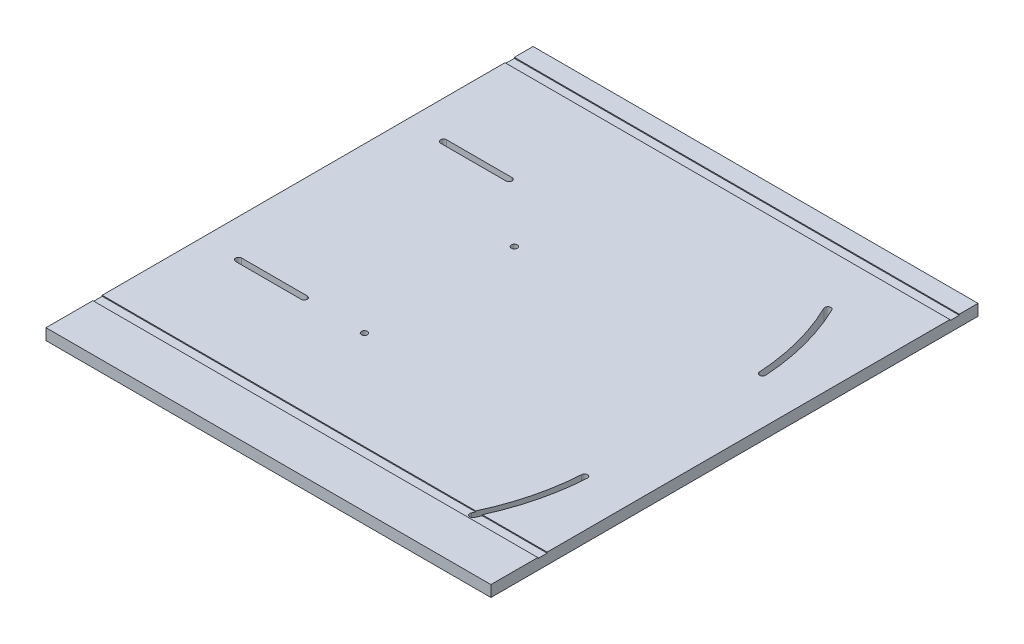
SolidWorks part; units mm, degrees
ref_plane "Front" through (0, 0, 0) normal (0, 0, 1) x (1, 0, 0)
ref_plane "Top" through (0, 0, 0) normal (0, 1, 0) x (1, 0, 0)
ref_plane "Right" through (0, 0, 0) normal (1, 0, 0) x (0, 0, -1)
sketch "Sketch1" plane through (0, 0, 0) normal (0, 1, 0) x (1, 0, 0)
  line L1 (-301.625, 330.2) -> (301.625, 330.2)
  line L2 (-301.625, 330.2) -> (-301.625, -330.2)
  line L3 (-301.625, -330.2) -> (301.625, -330.2)
  line L4 (301.625, 330.2) -> (301.625, -330.2)
  line L5 (-301.625, 330.2) -> (301.625, -330.2) construction
  line L6 (-301.625, -330.2) -> (301.625, 330.2) construction
  point P0 (0, 0)
  dimension "D1" = 660.4
  dimension "D2" = 603.25
extrude "Boss-Extrude1" add sketch "Sketch1" along normal blind 19.05
chamfer "Chamfer1" distance 3.81 angle 45 4 edges at (0, 0, -330.2) (-301.625, 0, 0) (0, 0, 330.2) (301.625, 0, 0)
sketch "Sketch8" plane through (0, 19.05, 0) normal (0, 1, 0) x (1, 0, 0)
  line L0 (301.625, 330.2) -> (-301.625, 330.2) construction
  line L1 (-103.505, 330.2) -> (-106.045, 330.2)
  line L2 (-103.505, 330.2) -> (-103.505, -330.2)
  line L3 (-103.505, -330.2) -> (-106.045, -330.2)
  line L4 (-106.045, 330.2) -> (-106.045, -330.2)
  line L5 (-301.625, -330.2) -> (301.625, -330.2) construction
  line L6 (301.625, -330.2) -> (301.625, 330.2) construction
  dimension "D1" = 2.54
  dimension "D2" = 405.13
sketch "Sketch3" plane through (0, 19.05, 0) normal (0, 1, 0) x (1, 0, 0)
  line L0 (-49.9149, 311.15) -> (-49.9149, -273.05) construction
  line L1 (301.625, -330.2) -> (301.625, 330.2) construction
  line L2 (-250.825, 157.9404) -> (-161.925, 157.9404) construction
  line L3 (-250.825, 162.0044) -> (-161.925, 162.0044)
  line L4 (-250.825, 153.8764) -> (-161.925, 153.8764)
  line L5 (-49.9149, 19.05) -> (-301.625, 19.05) construction
  line L6 (-250.825, -119.8404) -> (-161.925, -119.8404) construction
  line L7 (-250.825, -123.9044) -> (-161.925, -123.9044)
  line L8 (-250.825, -115.7764) -> (-161.925, -115.7764)
  line L9 (-301.625, 330.2) -> (-301.625, -330.2) construction
  line L11 (-301.625, 311.15) -> (301.625, 311.15) construction
  line L12 (301.625, 330.2) -> (-301.625, 330.2) construction
  line L13 (-301.625, -273.05) -> (301.625, -273.05) construction
  arc A0 (-250.825, 162.0044) -> (-250.825, 153.8764) centre (-250.825, 157.9404) ccw
  arc A1 (-161.925, 153.8764) -> (-161.925, 162.0044) centre (-161.925, 157.9404) ccw
  arc A2 (-250.825, -123.9044) -> (-250.825, -115.7764) centre (-250.825, -119.8404) cw
  arc A3 (-161.925, -115.7764) -> (-161.925, -123.9044) centre (-161.925, -119.8404) cw
  point P7 (-206.375, 157.9404)
  point P16 (-206.375, -119.8404)
  dimension "D1" = 8.128
  dimension "D2" = 88.9
  dimension "D3" = 95.25
  dimension "D4" = 19.05
  dimension "D5" = 584.2
extrude "Cut-Extrude2" cut sketch "Sketch3" against normal through all
sketch "Sketch6" plane through (0, 19.05, 0) normal (0, 1, 0) x (1, 0, 0)
  line L0 (-79.375, 82.55) -> (-79.375, -120.65) construction
  line L1 (301.625, -330.2) -> (301.625, 330.2) construction
  line L2 (-301.625, -330.2) -> (301.625, -330.2) construction
  circle A0 centre (-79.375, 82.55) radius 4.064
  circle A1 centre (-79.375, -120.65) radius 4.064
  dimension "D1" = 8.128
  dimension "D2" = 203.2
  dimension "D3" = 381
  dimension "D4" = 209.55
extrude "Cut-Extrude5" cut sketch "Sketch6" against normal through all
sketch "Sketch7" plane through (0, 19.05, 0) normal (0, 1, 0) x (1, 0, 0)
  line L0 (-79.375, 82.55) -> (148.3551, 82.55) construction
  line L2 (250.825, 82.55) -> (-79.375, 82.55) construction
  line L3 (-79.375, 82.55) -> (-79.375, -120.65) construction
  line L4 (-79.375, -19.05) -> (301.625, -19.05) construction
  line L5 (301.625, -330.2) -> (301.625, 330.2) construction
  arc A0 (250.825, 82.55) -> (219.8878, 222.0986) centre (-79.375, 82.55) ccw construction
  arc A1 (254, 82.55) -> (222.7654, 223.4404) centre (-79.375, 82.55) ccw
  arc A2 (247.65, 82.55) -> (217.0103, 220.7567) centre (-79.375, 82.55) ccw
  arc A3 (247.65, 82.55) -> (254, 82.55) centre (250.825, 82.55) ccw
  arc A4 (222.7654, 223.4404) -> (217.0103, 220.7567) centre (219.8878, 222.0986) ccw
  arc A5 (250.825, -120.65) -> (219.8878, -260.1986) centre (-79.375, -120.65) cw construction
  arc A6 (254, -120.65) -> (222.7654, -261.5404) centre (-79.375, -120.65) cw
  arc A7 (247.65, -120.65) -> (217.0103, -258.8567) centre (-79.375, -120.65) cw
  arc A8 (247.65, -120.65) -> (254, -120.65) centre (250.825, -120.65) cw
  arc A9 (222.7654, -261.5404) -> (217.0103, -258.8567) centre (219.8878, -260.1986) cw
  point P4 (242.9979, 154.0184)
  point P20 (242.9979, -192.1184)
  dimension "D1" = 3.175
  dimension "D2" = 330.2
  dimension "D3" = 25
  dimension "D4" = 0
sketch "Sketch9" plane through (0, 19.05, 0) normal (0, 1, 0) x (1, 0, 0)
  line L0 (-79.375, 82.55) -> (-79.375, -120.65) construction
  line L1 (-79.375, -19.05) -> (301.625, -19.05) construction
  line L3 (301.625, -330.2) -> (301.625, 330.2) construction
  line L5 (238.0619, 101.6) -> (301.625, 101.6) construction
  arc A0 (238.0619, -139.7) -> (206.6083, -259.7277) centre (-79.375, -120.65) cw construction
  arc A1 (242.1186, -139.9435) -> (210.2631, -261.5051) centre (-79.375, -120.65) cw
  arc A2 (234.0052, -139.4565) -> (202.9536, -257.9504) centre (-79.375, -120.65) cw
  arc A3 (234.0052, -139.4565) -> (242.1186, -139.9435) centre (238.0619, -139.7) cw
  arc A4 (238.0619, 101.6) -> (206.6083, 221.6277) centre (-79.375, 82.55) ccw construction
  arc A5 (242.1186, 101.8435) -> (210.2631, 223.4051) centre (-79.375, 82.55) ccw
  arc A6 (234.0052, 101.3565) -> (202.9536, 219.8504) centre (-79.375, 82.55) ccw
  arc A7 (234.0052, 101.3565) -> (242.1186, 101.8435) centre (238.0619, 101.6) ccw
  arc A8 (210.2631, 223.4051) -> (202.9536, 219.8504) centre (206.6083, 221.6277) ccw
  arc A9 (210.2631, -261.5051) -> (202.9536, -257.9504) centre (206.6083, -259.7277) cw
  point P9 (228.246, 163.1628)
  point P13 (228.246, -201.2628)
  dimension "D1" = 318.008
  dimension "D6" = 8.128
  dimension "D2" = 22.5
  dimension "D4" = 120.65
extrude "Cut-Extrude8" cut sketch "Sketch9" against normal through all
sketch "Sketch10" plane through (0, 19.05, 0) normal (0, 1, 0) x (1, 0, 0)
  line L0 (-301.625, 304.8) -> (301.625, 304.8)
  line L1 (-301.625, 304.8) -> (-301.625, 292.1)
  line L2 (301.625, 304.8) -> (301.625, 292.1)
  line L3 (-301.625, 292.1) -> (301.625, 292.1)
  line L4 (-301.625, 330.2) -> (-301.625, -330.2) construction
  line L5 (301.625, -330.2) -> (301.625, 330.2) construction
  line L6 (-301.625, -254) -> (301.625, -254)
  line L7 (-301.625, -254) -> (-301.625, -266.7)
  line L8 (301.625, -254) -> (301.625, -266.7)
  line L9 (-301.625, -266.7) -> (301.625, -266.7)
  line L10 (301.625, 330.2) -> (-301.625, 330.2) construction
  line L11 (-301.625, -330.2) -> (301.625, -330.2) construction
  dimension "D1" = 12.7
  dimension "D2" = 12.7
  dimension "D3" = 25.4
  dimension "D4" = 63.5
extrude "Cut-Extrude9" cut sketch "Sketch10" against normal blind 1.27
